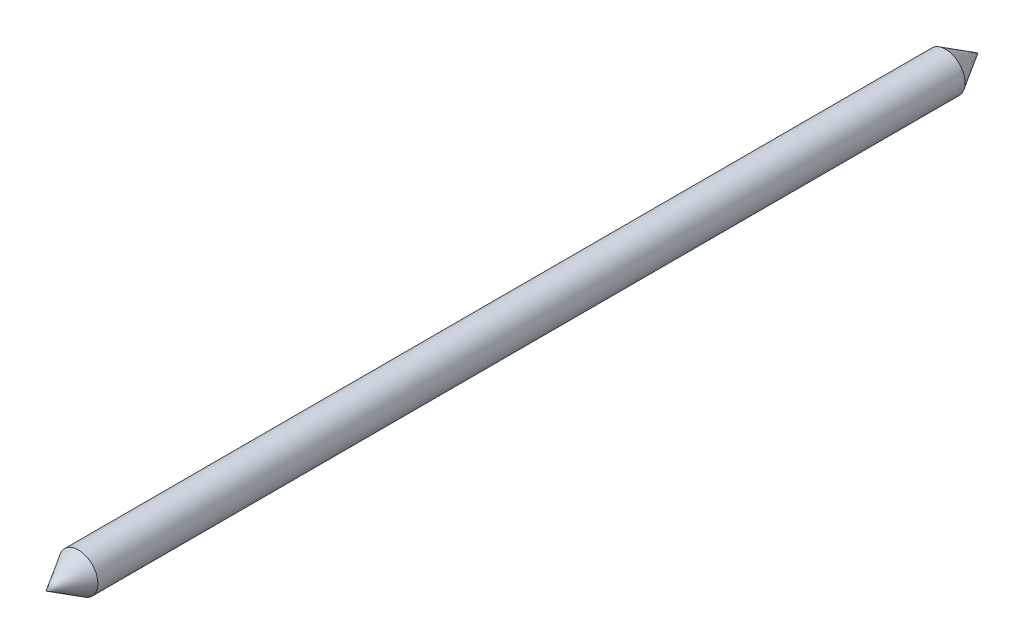
SolidWorks part; units mm, degrees
ref_plane "Front Plane" through (0, 0, 0) normal (0, 0, 1) x (1, 0, 0)
ref_plane "Top Plane" through (0, 0, 0) normal (0, 1, 0) x (1, 0, 0)
ref_plane "Right Plane" through (0, 0, 0) normal (1, 0, 0) x (0, 0, -1)
sketch "Sketch1" plane through (0, 0, 0) normal (0, 1, 0) x (1, 0, 0)
  line L0 (0, 182.5625) -> (0, -182.5625)
  line L1 (0, -182.5625) -> (7.62, -169.8625)
  line L2 (7.62, -169.8625) -> (7.62, 169.8625)
  line L3 (7.62, 169.8625) -> (0, 182.5625)
  point P2 (0, 0)
  point P6 (7.62, 0)
  dimension "D1" = 365.125
  dimension "D2" = 7.62
  dimension "D3" = 12.7
revolve "Revolve1" add sketch "Sketch1" angle 360 about L0
